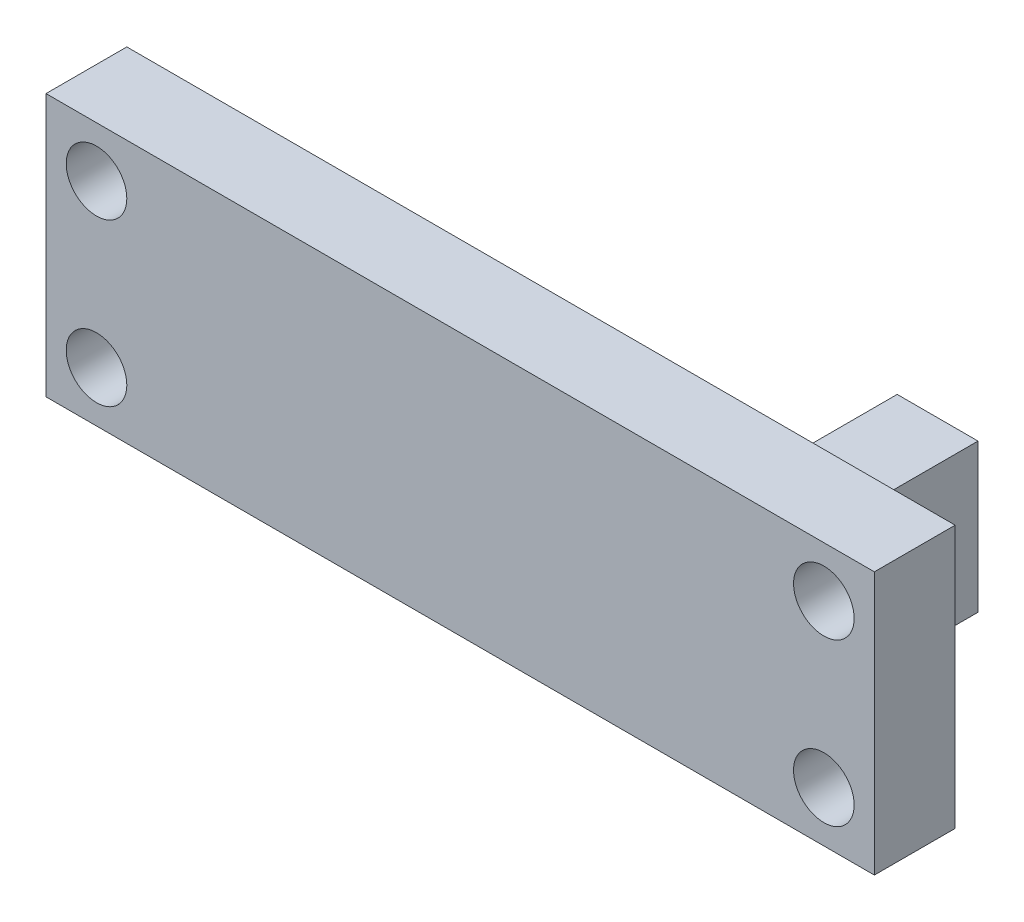
SolidWorks part; units mm, degrees
ref_plane "Alzado" through (0, 0, 0) normal (0, 0, 1) x (1, 0, 0)
ref_plane "Planta" through (0, 0, 0) normal (0, 1, 0) x (1, 0, 0)
ref_plane "Vista lateral" through (0, 0, 0) normal (1, 0, 0) x (0, 0, -1)
sketch "Croquis1" plane through (0, 0, 0) normal (0, 0, 1) x (1, 0, 0)
  line L1 (-41, 13) -> (0, 13)
  line L2 (-41, 13) -> (-41, 0)
  line L3 (-41, 0) -> (0, 0)
  line L4 (0, 13) -> (0, 0)
  dimension "D1" = 13
  dimension "D2" = 41
  dimension "D3" = 0
  dimension "D4" = 0
extrude "Saliente-Extruir1" add sketch "Croquis1" along normal blind 4
sketch "Croquis2" plane through (0, 0, 4) normal (0, 0, 1) x (1, 0, 0)
  line L0 (0, 0) -> (0, 13) construction
  line L1 (0, 13) -> (-41, 13) construction
  line L2 (-41, 0) -> (0, 0) construction
  line L3 (-41, 13) -> (-41, 0) construction
  line L4 (-38.5, 10.5) -> (-2.5, 10.5) construction
  line L5 (-38.5, 10.5) -> (-38.5, 2.5) construction
  circle A0 centre (-2.5, 10.5) radius 1.5
  circle A1 centre (-2.5, 2.5) radius 1.5
  circle A2 centre (-38.5, 10.5) radius 1.5
  circle A3 centre (-38.5, 2.5) radius 1.5
  dimension "D1" = 3
  dimension "D2" = 3
  dimension "D3" = 3
  dimension "D4" = 3
  dimension "D5" = 2.5
  dimension "D6" = 2.5
  dimension "D7" = 2.5
  dimension "D8" = 2.5
  dimension "D9" = 2.5
  dimension "D10" = 2.5
  dimension "D11" = 2.5
  dimension "D12" = 2.5
extrude "Cortar-Extruir1" cut sketch "Croquis2" against normal through all
sketch "Croquis3" plane through (0, 0, 0) normal (0, 0, -1) x (-1, 0, 0)
  line L0 (0, 0) -> (0, 13) construction
  line L1 (5.87, 10.17) -> (9.87, 10.17)
  line L2 (5.87, 10.17) -> (5.87, 2.83)
  line L3 (5.87, 2.83) -> (9.87, 2.83)
  line L4 (9.87, 10.17) -> (9.87, 2.83)
  line L6 (0, 13) -> (41, 13) construction
  dimension "D1" = 4
  dimension "D2" = 7.34
  dimension "D3" = 2.83
  dimension "D4" = 5.87
extrude "Saliente-Extruir2" add sketch "Croquis3" along normal blind 7
